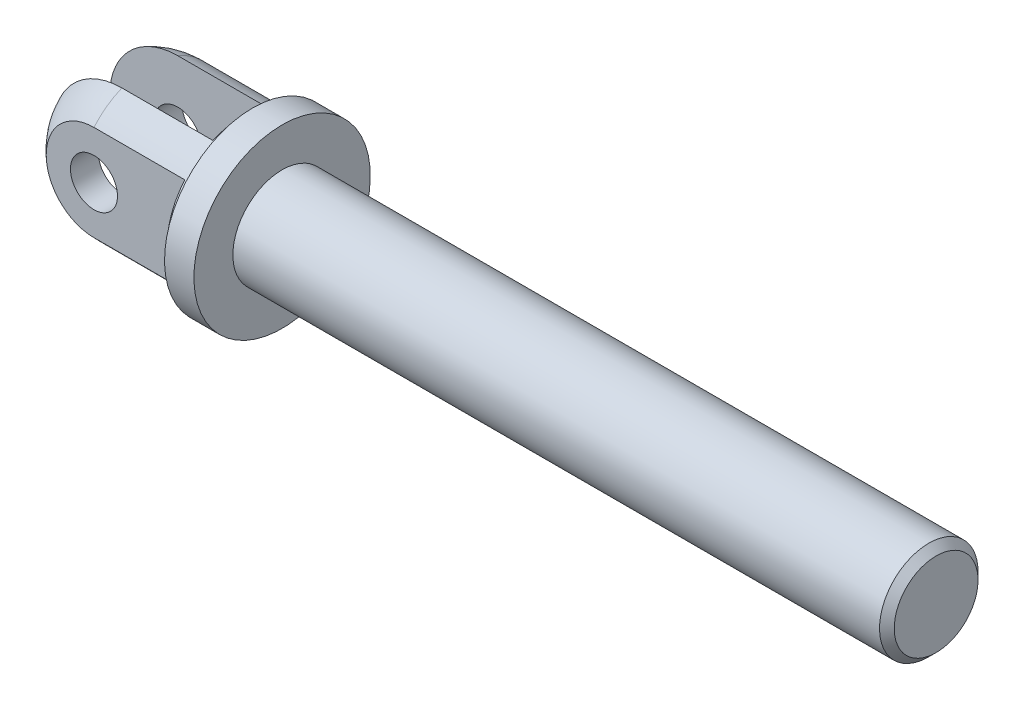
SolidWorks part; units mm, degrees
ref_plane "前视基准面" through (0, 0, 0) normal (0, 0, 1) x (1, 0, 0)
ref_plane "上视基准面" through (0, 0, 0) normal (0, 1, 0) x (1, 0, 0)
ref_plane "右视基准面" through (0, 0, 0) normal (1, 0, 0) x (0, 0, -1)
sketch "草图2" plane through (0, 0, -1.8) normal (0, 0, 1) x (1, 0, 0)
  line L0 (6.7, 5) -> (13.7, 5)
  line L1 (13.7, 5) -> (13.7, 6)
  line L2 (13.7, 6) -> (15.7, 6)
  line L3 (15.7, 6) -> (15.7, 3.35)
  line L4 (15.7, 3.35) -> (59.7, 3.35)
  line L5 (60.2, 2.85) -> (60.2, 0)
  line L6 (60.2, 0) -> (1.7, 0)
  line L7 (59.7, 3.35) -> (60.2, 2.85)
  arc A0 (6.7, 5) -> (1.7, 0) centre (6.7, 0) ccw
  point P5 (60.2, 3.35)
  dimension "D1" = 53.5
  dimension "D2" = 7
  dimension "D3" = 2
  dimension "D4" = 3.35
  dimension "D5" = 6
  dimension "D6" = 5
revolve "旋转1" add sketch "草图2" angle 360 about L6
sketch "草图3" plane through (0, 0, -1.8) normal (0, 1, 0) x (1, 0, 0)
  line L1 (2.6168, -5.2048) -> (12.8778, -5.2048)
  line L2 (2.6168, -5.2048) -> (2.6168, -3.8)
  line L3 (2.6168, -3.8) -> (12.8778, -3.8)
  line L4 (12.8778, -5.2048) -> (12.8778, -3.8)
  line L5 (13.7, 0) -> (7.8186, 0) construction
  line L6 (13.7, 6) -> (13.7, -6) construction
  line L7 (12.8778, 5.2048) -> (12.8778, 3.8)
  line L8 (2.6168, 3.8) -> (12.8778, 3.8)
  line L9 (2.6168, 5.2048) -> (2.6168, 3.8)
  line L10 (2.6168, 5.2048) -> (12.8778, 5.2048)
  line L11 (6.7, -5) -> (13.7, -5) construction
  dimension "D1" = 1.2
extrude "切除-拉伸1" cut sketch "草图3" against normal mid plane 100
sketch "草图4" plane through (0, 0, 0) normal (0, 1, 0) x (1, 0, 0)
  line L0 (6.7, 3.6) -> (0, 3.6) construction
  line L1 (1.6713, 3.7) -> (12.8778, 3.7)
  line L2 (1.6713, 3.7) -> (1.6713, -0.1)
  line L3 (1.6713, -0.1) -> (12.8778, -0.1)
  line L4 (12.8778, 3.7) -> (12.8778, -0.1)
  line L5 (6.7, 0) -> (0, 0) construction
  dimension "D1" = 0.1
  dimension "D2" = 0.1
extrude "切除-拉伸2" cut sketch "草图4" against normal mid plane 100
sketch "草图7" plane through (0, 0, 2) normal (0, 0, 1) x (1, 0, 0)
  circle A0 centre (6.7, 0) radius 1.6
extrude "切除-拉伸4" cut sketch "草图7" against normal through all
